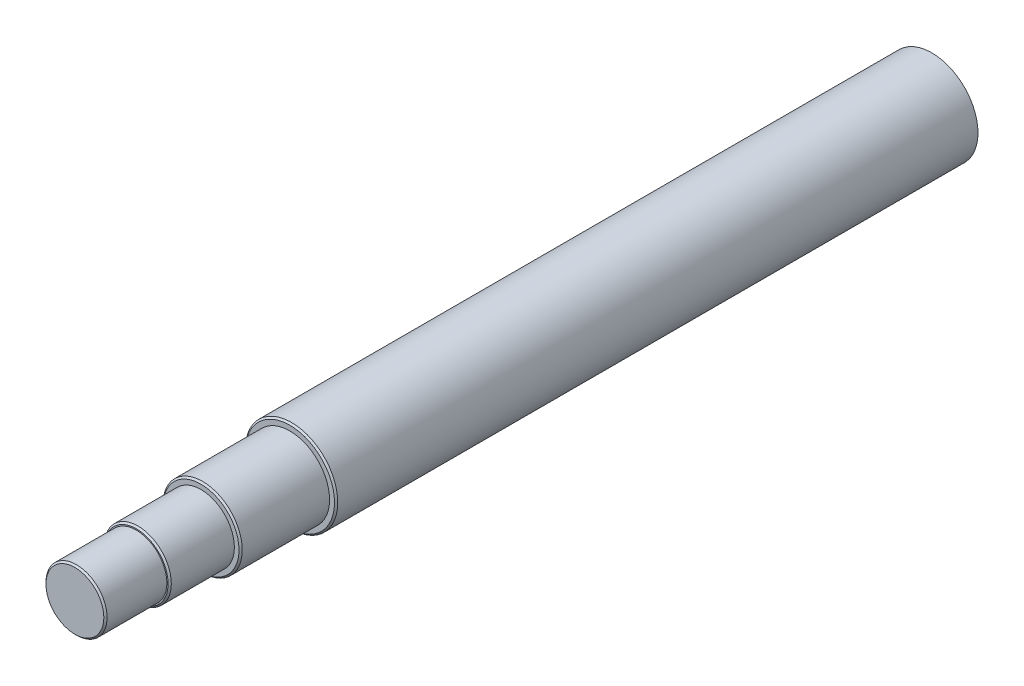
SolidWorks part; units mm, degrees
ref_plane "Płaszczyzna przednia" through (0, 0, 0) normal (0, 0, 1) x (1, 0, 0)
ref_plane "Płaszczyzna górna" through (0, 0, 0) normal (0, 1, 0) x (1, 0, 0)
ref_plane "Płaszczyzna prawa" through (0, 0, 0) normal (1, 0, 0) x (0, 0, -1)
sketch "Szkic1" plane through (0, 0, 0) normal (0, 0, 1) x (1, 0, 0)
  circle A0 centre (0, 0) radius 28.575
  dimension "D1" = 57.15
extrude "Dodanie-wyciągnięcie1" add sketch "Szkic1" along normal blind 530
sketch "Szkic2" plane through (0, 0, 530) normal (0, 0, 1) x (1, 0, 0)
  circle A0 centre (0, 0) radius 18.9
  dimension "D1" = 37.8
extrude "Wytnij-wyciągnięcie1" cut sketch "Szkic2" against normal blind 38 flip side to cut contours A0
sketch "Szkic3" plane through (0, 0, 492) normal (0, 0, 1) x (1, 0, 0)
  circle A0 centre (0, 0) radius 20.64
  circle A1 centre (0, 0) radius 18.9 construction
  circle A2 centre (0, 0) radius 18.9
  dimension "D1" = 41.28
extrude "Wytnij-wyciągnięcie2" cut sketch "Szkic3" against normal blind 40 flip side to cut
sketch "Szkic4" plane through (0, 0, 452) normal (0, 0, 1) x (1, 0, 0)
  circle A0 centre (0, 0) radius 24.5
  dimension "D1" = 49
extrude "Wytnij-wyciągnięcie3" cut sketch "Szkic4" against normal blind 55 flip side to cut
sketch "Szkic5" plane through (0, 0, 0) normal (0, 0, -1) x (-1, 0, 0)
  circle A0 centre (0, 0) radius 5
  dimension "D1" = 10
extrude "Dodanie-wyciągnięcie2" add sketch "Szkic5" along normal blind 5
chamfer "Sfazowanie1" distance 1 angle 45 1 edges at (18.9, 0, 530)
chamfer "Sfazowanie2" distance 1 angle 45 3 edges at (28.575, 0, 397) (24.5, 0, 452) (20.64, 0, 492)
